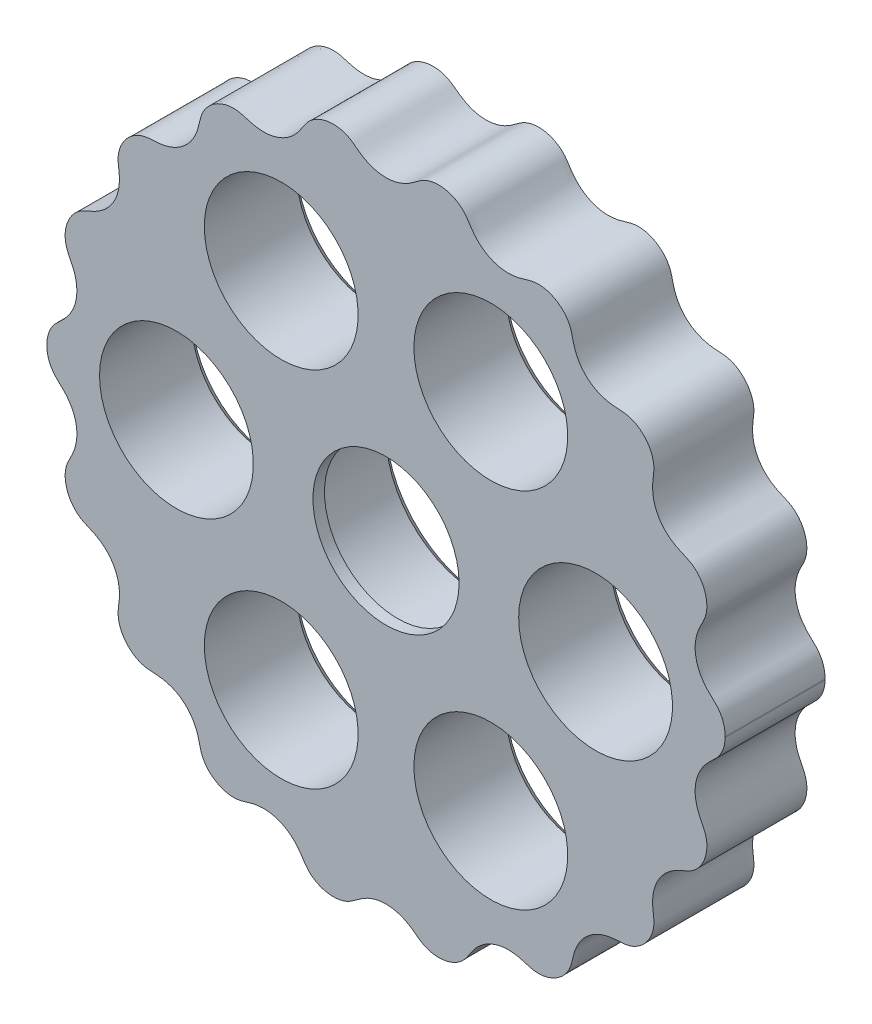
SolidWorks part; units mm, degrees
ref_plane "Front Plane" through (0, 0, 0) normal (0, 0, 1) x (1, 0, 0)
ref_plane "Top Plane" through (0, 0, 0) normal (0, 1, 0) x (1, 0, 0)
ref_plane "Right Plane" through (0, 0, 0) normal (1, 0, 0) x (0, 0, -1)
sketch "Sketch1" plane through (0, 0, 0) normal (0, 0, 1) x (1, 0, 0)
  arc A0 (44.0985, -0.1203) -> (44.1, 0) centre (39.3924, 0) ccw
  circle A1 centre (0, 0) radius 12
  circle A2 centre (27.25, 0) radius 10
  circle A3 centre (13.625, -23.5992) radius 10
  circle A4 centre (-13.625, -23.5992) radius 10
  circle A5 centre (-27.25, 0) radius 10
  circle A6 centre (-13.625, 23.5992) radius 10
  circle A7 centre (13.625, 23.5992) radius 10
  spline S0 degree 4 poles (36.6767, -18.9558) (36.8635, -18.7987) (37.1568, -18.579) (37.5707, -18.3184) (38.1155, -18.0434) (38.5626, -17.8474) (39.0142, -17.663) (39.4567, -17.456) (39.9012, -17.1807) (40.3307, -16.827) (40.8354, -16.2774) (41.3043, -15.523) (41.6465, -14.5868) (41.7649, -13.5582) (41.6813, -12.7422) (41.4951, -12.1162) (41.2986, -11.6694) (41.1215, -11.3218) (40.8977, -10.8888) (40.649, -10.3583) (40.4142, -9.7146) (40.1974, -8.7592) (40.1486, -7.6129) (40.3906, -6.3196) (40.9635, -5.1322) (41.587, -4.3265) (42.1201, -3.7892) (42.487, -3.4498) (42.7801, -3.1781) (43.1277, -2.8182) (43.4078, -2.4428) (43.6222, -2.0645) (43.7821, -1.6974) (43.8734, -1.446) (43.9495, -1.19) (44.0102, -0.9293) (44.0501, -0.6984) (44.0747, -0.5033) (44.0889, -0.3315) (44.0965, -0.1882) (44.1004, -0.0512) (44.1003, 0.0575) (44.0961, 0.2002) (44.0877, 0.3516) (44.0718, 0.5312) (44.0443, 0.7371) (44.0062, 0.9465) (43.9574, 1.1527) (43.9002, 1.3564) (43.8124, 1.6248) (43.6759, 1.9561) (43.4704, 2.3388) (43.1973, 2.7268) (42.9028, 3.0591) (42.5811, 3.3642) (42.2543, 3.6633) (41.857, 4.0496) (41.4472, 4.5088) (41.0516, 5.0585) (40.6188, 5.8583) (40.2694, 6.862) (40.1379, 7.9369) (40.2404, 9.0241) (40.4824, 9.9238) (40.7241, 10.5303) (40.9711, 11.0329) (41.23, 11.5305) (41.4742, 12.0369) (41.6912, 12.7506) (41.7643, 13.6759) (41.6231, 14.6695) (41.2345, 15.6741) (40.6786, 16.4957) (40.0904, 17.0544) (39.5529, 17.4028) (39.1287, 17.6105) (38.7812, 17.7582) (38.3459, 17.9401) (37.6896, 18.2421) (36.8537, 18.748) (35.9651, 19.5642) (35.2253, 20.6754) (34.8042, 21.8218) (34.6582, 22.7995) (34.6551, 23.5837) (34.7014, 24.1649) (34.7588, 24.6276) (34.819, 25.0899) (34.8465, 25.5562) (34.8182, 26.0519) (34.7221, 26.5691) (34.5055, 27.2363) (34.094, 28.0103) (33.4389, 28.7967) (32.6453, 29.3765) (31.9237, 29.701) (31.3397, 29.8541) (30.9247, 29.9174) (30.5063, 29.9454) (30.0877, 29.9633) (29.5648, 29.9977) (28.7961, 30.0962) (27.8011, 30.3642) (26.6402, 30.9641) (25.5501, 31.9548) (24.8466, 33.0536) (24.4844, 34.0219) (24.3027, 34.7493) (24.1799, 35.3002) (24.0444, 35.8492) (23.7558, 36.5419) (23.2182, 37.3055) (22.4721, 37.981) (21.5304, 38.5043) (20.5803, 38.7796) (19.7758, 38.834) (19.1432, 38.7607) (18.6866, 38.6509) (18.3273, 38.5424) (17.8796, 38.4022) (17.1879, 38.2098) (16.2295, 38.0541) (15.1511, 38.0927) (14.1001, 38.3568) (13.249, 38.7395) (12.5843, 39.159) (11.9777, 39.6706) (11.5076, 40.1878) (11.1477, 40.6723) (10.8676, 41.0971) (10.6491, 41.4405) (10.4195, 41.7769) (10.1616, 42.0928) (9.8452, 42.4081) (9.4641, 42.7096) (8.8955, 43.0565) (8.1021, 43.3731) (7.1136, 43.5515) (6.147, 43.4906) (5.3888, 43.281) (4.8443, 43.0283) (4.4861, 42.8141) (4.1483, 42.5698) (3.8181, 42.3158) (3.399, 42.0065) (2.753, 41.5865) (1.827, 41.1474) (0.5868, 40.8561) (-0.8258, 40.8878) (-2.0369, 41.2268) (-2.9229, 41.6848) (-3.5391, 42.1066) (-3.9385, 42.4083) (-4.2568, 42.6512) (-4.5868, 42.8786) (-4.9366, 43.0749) (-5.4733, 43.3086) (-6.2224, 43.5002) (-7.1565, 43.5453) (-8.2308, 43.3442) (-9.1419, 42.9461) (-9.7919, 42.4774) (-10.2304, 42.0207) (-10.5107, 41.6472) (-10.716, 41.3356) (-10.9671, 40.9426) (-11.3683, 40.3523) (-11.9933, 39.6173) (-12.9784, 38.8345) (-14.3072, 38.2427) (-15.622, 38.0386) (-16.7078, 38.119) (-17.5001, 38.2943) (-18.0183, 38.4446) (-18.4296, 38.575) (-18.8445, 38.6948) (-19.2689, 38.7773) (-19.7296, 38.8158) (-20.2217, 38.799) (-20.8742, 38.6969) (-21.6651, 38.435) (-22.5148, 37.9532) (-23.2004, 37.3139) (-23.6407, 36.7001) (-23.8979, 36.1889) (-24.0388, 35.8228) (-24.1457, 35.4456) (-24.2324, 35.0637) (-24.341, 34.5862) (-24.5432, 33.8399) (-24.9478, 32.8575) (-25.7396, 31.7268) (-26.8198, 30.8543) (-27.9055, 30.3412) (-28.8681, 30.0882) (-29.542, 29.9965) (-30.1085, 29.9625) (-30.655, 29.9382) (-31.2013, 29.8918) (-31.908, 29.7209) (-32.7236, 29.3297) (-33.437, 28.7738) (-34.0217, 28.0893) (-34.4319, 27.3875) (-34.6947, 26.7092) (-34.8184, 26.0998) (-34.8448, 25.586) (-34.8229, 25.1791) (-34.7914, 24.879) (-34.753, 24.5799) (-34.7164, 24.2805) (-34.6791, 23.9054) (-34.6547, 23.4533) (-34.6644, 22.9248) (-34.752, 22.1746) (-34.9928, 21.2469) (-35.4949, 20.1956) (-36.285, 19.2336) (-37.1129, 18.5857) (-37.8164, 18.1869) (-38.3337, 17.9455) (-38.7546, 17.7691) (-39.1754, 17.5922) (-39.5824, 17.3838) (-39.9866, 17.1147) (-40.376, 16.7794) (-40.8341, 16.2703) (-41.287, 15.5514) (-41.6373, 14.6281) (-41.7684, 13.5957) (-41.6841, 12.7484) (-41.4922, 12.1084) (-41.2953, 11.6627) (-41.1183, 11.3156) (-40.8949, 10.8831) (-40.6493, 10.3583) (-40.4186, 9.7263) (-40.2044, 8.7952) (-40.1455, 7.6523) (-40.3811, 6.3316) (-40.9655, 5.1189) (-41.6171, 4.2907) (-42.1615, 3.7501) (-42.5188, 3.4208) (-42.8029, 3.1556) (-43.1388, 2.8039) (-43.5356, 2.2681) (-43.902, 1.5016) (-44.1301, 0.4873) (-44.1153, -0.4997) (-43.9342, -1.3305) (-43.676, -1.9663) (-43.4233, -2.4149) (-43.1338, -2.8061) (-42.8211, -3.1409) (-42.4852, -3.4513) (-42.1496, -3.7619) (-41.7459, -4.1672) (-41.2216, -4.785) (-40.6667, -5.6805) (-40.2571, -6.8575) (-40.1492, -8.0179) (-40.2435, -8.9709) (-40.4198, -9.7036) (-40.5923, -10.2019) (-40.7703, -10.617) (-40.9338, -10.9558) (-41.0705, -11.2238) (-41.2084, -11.4912) (-41.3399, -11.762) (-41.4983, -12.1364) (-41.6474, -12.6276) (-41.7379, -13.2414) (-41.7216, -13.967) (-41.5738, -14.7731) (-41.2501, -15.6297) (-40.7493, -16.4152) (-40.1472, -17.0103) (-39.5948, -17.3794) (-39.1613, -17.5962) (-38.805, -17.7483) (-38.3581, -17.9346) (-37.6632, -18.2533) (-36.7684, -18.8026) (-35.9394, -19.6017) (-35.3162, -20.559) (-34.9501, -21.4361) (-34.754, -22.1735) (-34.6561, -22.9355) (-34.6539, -23.6107) (-34.7037, -24.19) (-34.7654, -24.6746) (-34.814, -25.0624) (-34.8415, -25.4527) (-34.8332, -25.844) (-34.765, -26.411) (-34.56, -27.1363) (-34.1301, -27.9767) (-33.4866, -28.7263) (-32.8171, -29.248) (-32.2156, -29.5706) (-31.7373, -29.7537) (-31.2675, -29.87) (-30.8155, -29.9284) (-30.361, -29.9515) (-29.9067, -29.9728) (-29.3398, -30.0211) (-28.5445, -30.1517) (-27.5467, -30.4714) (-26.4782, -31.095) (-25.6473, -31.8986) (-25.1024, -32.6745) (-24.7614, -33.3361) (-24.5688, -33.82) (-24.4344, -34.2453) (-24.3393, -34.6045) (-24.2708, -34.8937) (-24.2056, -35.1836) (-24.1369, -35.4728) (-24.0508, -35.7776) (-23.9368, -36.0939) (-23.7481, -36.5019) (-23.4494, -36.98) (-23.0222, -37.4813) (-22.3719, -38.029) (-21.544, -38.4954) (-20.7168, -38.7507) (-19.9455, -38.8252) (-19.36, -38.7875) (-18.9635, -38.7214) (-18.575, -38.6194) (-18.1922, -38.4994) (-17.7124, -38.3527) (-16.9871, -38.1681) (-15.9954, -38.0433) (-14.7404, -38.1435) (-13.4038, -38.602) (-12.3415, -39.3031) (-11.6253, -40.033) (-11.1642, -40.6483) (-10.8775, -41.0818) (-10.6541, -41.4324) (-10.3623, -41.8626) (-9.899, -42.3938) (-9.1869, -42.9321) (-8.2037, -43.3602) (-7.0734, -43.5529) (-6.1148, -43.4841) (-5.3713, -43.274) (-4.8379, -43.0245) (-4.4874, -42.8146) (-4.1564, -42.5758) (-3.8331, -42.3273) (-3.4233, -42.0238) (-2.7537, -41.584) (-1.7612, -41.114) (-0.4425, -40.8308) (1.0403, -40.9203) (2.2524, -41.3176) (3.0965, -41.7927) (3.6787, -42.2102) (4.0505, -42.4945) (4.3506, -42.7186) (4.7419, -42.9762) (5.3109, -43.2592) (6.0842, -43.4809) (7.0779, -43.5461) (8.1565, -43.3701) (9.0185, -43.0112) (9.656, -42.5787) (10.0808, -42.1789) (10.3429, -41.8772) (10.5757, -41.5527) (10.7913, -41.217) (11.062, -40.7981) (11.4933, -40.1917) (12.1633, -39.458) (13.1794, -38.7205) (14.4926, -38.1994) (15.7586, -38.0413) (16.7829, -38.1326) (17.5369, -38.3043) (18.0387, -38.4511) (18.4373, -38.5773) (18.8393, -38.693) (19.2503, -38.7741) (19.7068, -38.8152) (20.2045, -38.8013) (20.8784, -38.6982) (21.7056, -38.4205) (22.4637, -37.9777) (23.1147, -37.3897) (23.5463, -36.8348) (23.8129, -36.3801) (24.0082, -35.9224) (24.1409, -35.4736) (24.2423, -35.0176) (24.3472, -34.5622) (24.5038, -33.9993) (24.7774, -33.2626) (25.2526, -32.3934) (26.0445, -31.4622) (27.1225, -30.6755) (28.2369, -30.2168) (29.1936, -30.0303) (29.912, -29.9724) (30.3823, -29.9506) (30.7585, -29.9304) (31.2269, -29.8792) (31.8494, -29.734) (32.5908, -29.4093) (33.3924, -28.8267) (34.1, -28.0146) (34.5716, -27.1275) (34.818, -26.2303) (34.8559, -25.4836) (34.798, -24.9232) (34.725, -24.3656) (34.6454, -23.6229) (34.6499, -22.5928) (34.9244, -21.3341) (35.5841, -20.0498) (36.4432, -19.0874) (37.2687, -18.4847) (37.9615, -18.1146) (38.4661, -17.8887) (38.8747, -17.7199) (39.2802, -17.5429) (39.6692, -17.3307) (40.0569, -17.059) (40.4321, -16.7224) (40.8754, -16.2125) (41.3225, -15.4793) (41.6159, -14.6641) (41.7389, -13.805) (41.7166, -13.1062) (41.6324, -12.5888) (41.4921, -12.1142) (41.3092, -11.6862) (41.0959, -11.2734) (40.8838, -10.86) (40.6409, -10.3322) (40.3736, -9.5978) (40.1722, -8.6335) (40.1685, -7.4139) (40.4758, -6.1143) (41.0266, -5.0381) (41.638, -4.2711) (42.152, -3.7595) (42.4998, -3.4381) (42.7773, -3.1801) (43.1073, -2.8399) (43.4176, -2.4332) (43.6529, -2.012) (43.8242, -1.5939) (43.9238, -1.2824) (43.9889, -1.0282) (44.033, -0.8034) (44.0616, -0.6126) (44.0796, -0.4441) (44.0904, -0.304) (44.0975, -0.1709) (44.1002, -0.0646) (44.0998, 0.0735) (44.0955, 0.2206) (44.0851, 0.3964) (44.0643, 0.597) (44.0285, 0.8351) (43.9716, 1.1035) (43.8986, 1.3677) (43.8096, 1.6271) (43.6583, 1.9911) (43.4135, 2.4438) (43.0871, 2.8775) (42.6816, 3.2715) (42.2656, 3.653) (41.7268, 4.1708) (41.0686, 4.9615) (40.4759, 6.0882) (40.1559, 7.4652) (40.1801, 8.7282) (40.4033, 9.7014) (40.6813, 10.4269) (40.92, 10.9322) (41.1253, 11.3291) (41.3284, 11.7273) (41.5005, 12.1406) (41.6361, 12.607) (41.7187, 13.1243) (41.7383, 13.8359) (41.6034, 14.7228) (41.2341, 15.7008) (40.6514, 16.5314) (40.0399, 17.0906) (39.4907, 17.4365) (39.0646, 17.6413) (38.6279, 17.8207) (38.1942, 18.0075) (37.6639, 18.2672) (37.259, 18.512) (36.9707, 18.7184) (36.7863, 18.8659) knots 0 0 0 0 0 0.002836 0.004253 0.005671 0.007089 0.008507 0.009925 0.011343 0.013148 0.014954 0.018566 0.021594 0.024621 0.026888 0.028021 0.029155 0.030288 0.031421 0.033688 0.03596 0.038232 0.042776 0.046922 0.051068 0.053391 0.054552 0.055714 0.056876 0.058037 0.060361 0.061137 0.061913 0.062689 0.063466 0.064242 0.065018 0.065406 0.065795 0.066183 0.066571 0.066981 0.067391 0.067801 0.068211 0.069031 0.069851 0.070261 0.070671 0.071491 0.073132 0.074419 0.075707 0.076995 0.078282 0.07957 0.080858 0.083433 0.085425 0.087418 0.091402 0.095715 0.097871 0.100027 0.102202 0.103289 0.104376 0.106551 0.108726 0.111902 0.115078 0.118109 0.12114 0.123333 0.12443 0.125527 0.126624 0.127721 0.129914 0.133921 0.137927 0.141605 0.145284 0.147993 0.149348 0.150703 0.152057 0.153412 0.154767 0.156121 0.157815 0.159508 0.162895 0.166245 0.169595 0.170813 0.17203 0.173248 0.174466 0.175684 0.176902 0.179337 0.183463 0.187589 0.191926 0.196263 0.19845 0.199544 0.200638 0.202826 0.205013 0.208208 0.211403 0.214416 0.217428 0.219609 0.2207 0.22179 0.222881 0.223971 0.226152 0.230133 0.234114 0.236391 0.238667 0.240943 0.24322 0.245585 0.246768 0.247951 0.249134 0.250316 0.251499 0.252682 0.254316 0.255951 0.25922 0.262551 0.265882 0.267093 0.268303 0.269514 0.270725 0.271935 0.273146 0.275567 0.279672 0.283776 0.287796 0.291816 0.294143 0.295306 0.29647 0.297633 0.298797 0.29996 0.301124 0.304426 0.307727 0.310722 0.313717 0.315886 0.31697 0.318054 0.319138 0.320223 0.322391 0.326347 0.330303 0.334707 0.33911 0.341618 0.342872 0.344126 0.34538 0.346634 0.347888 0.349142 0.350743 0.352343 0.355544 0.35877 0.361996 0.363134 0.364272 0.36541 0.366548 0.367686 0.368824 0.3711 0.375531 0.379962 0.384669 0.387023 0.389377 0.391497 0.392557 0.393618 0.395738 0.397859 0.400955 0.404052 0.406156 0.40826 0.410365 0.412469 0.413345 0.414222 0.415098 0.415975 0.416851 0.417727 0.41948 0.421233 0.422985 0.426491 0.43057 0.434649 0.437302 0.438628 0.439954 0.44128 0.442607 0.443933 0.445259 0.446911 0.448564 0.451868 0.455076 0.458283 0.460547 0.461678 0.46281 0.463942 0.465074 0.467337 0.46954 0.471743 0.476148 0.480544 0.48494 0.487199 0.488328 0.489458 0.490587 0.491717 0.493975 0.497176 0.500376 0.503687 0.505343 0.506999 0.508328 0.509657 0.510985 0.512314 0.513643 0.514972 0.51763 0.521717 0.525805 0.529302 0.531051 0.5328 0.534548 0.535423 0.536297 0.537171 0.538046 0.53892 0.539794 0.541894 0.543993 0.546093 0.548193 0.551381 0.55457 0.556821 0.557947 0.559072 0.560198 0.561324 0.563575 0.567955 0.572335 0.574545 0.576756 0.578967 0.581177 0.583449 0.584584 0.58572 0.586856 0.587991 0.589127 0.590263 0.593481 0.5967 0.599994 0.601641 0.603287 0.604609 0.605931 0.607253 0.608575 0.609897 0.611219 0.613863 0.617928 0.621994 0.625448 0.627175 0.628902 0.630629 0.631492 0.632356 0.63322 0.634083 0.634947 0.63581 0.636899 0.637987 0.640164 0.64234 0.644517 0.647826 0.651135 0.652301 0.653467 0.654633 0.655799 0.656965 0.658131 0.660463 0.664492 0.668521 0.672617 0.676713 0.679129 0.680337 0.681545 0.682753 0.683961 0.686377 0.689701 0.693025 0.6963 0.699576 0.700761 0.701947 0.703132 0.704317 0.705502 0.706687 0.709058 0.71362 0.718182 0.722153 0.726125 0.728301 0.729389 0.730477 0.731565 0.732653 0.73483 0.737836 0.740842 0.744132 0.747422 0.748581 0.74974 0.7509 0.752059 0.753218 0.754378 0.756697 0.760702 0.764708 0.768825 0.772943 0.775373 0.776588 0.777804 0.779019 0.780234 0.781449 0.782664 0.784335 0.786007 0.789349 0.792743 0.79444 0.796137 0.797495 0.798852 0.80021 0.801567 0.802925 0.804282 0.806998 0.810684 0.81437 0.818367 0.822363 0.824552 0.825646 0.826741 0.827835 0.82893 0.831119 0.834143 0.837166 0.84035 0.843533 0.845713 0.847892 0.848982 0.850072 0.852251 0.856573 0.860895 0.864871 0.868848 0.871417 0.872702 0.873987 0.875272 0.876557 0.877842 0.879127 0.880763 0.8824 0.885674 0.889049 0.890737 0.892425 0.893775 0.895125 0.896475 0.897825 0.899175 0.900525 0.903225 0.906891 0.910557 0.914579 0.9186 0.920802 0.921903 0.923004 0.924105 0.925206 0.927407 0.928928 0.929689 0.930449 0.93121 0.93197 0.93235 0.93273 0.933111 0.933491 0.933889 0.934287 0.934686 0.935084 0.93588 0.936677 0.937473 0.938269 0.939066 0.939862 0.94205 0.944237 0.945331 0.946425 0.948612 0.952921 0.957229 0.96105 0.964871 0.967468 0.968766 0.970065 0.971364 0.972662 0.973961 0.97526 0.976997 0.978734 0.982209 0.985617 0.989025 0.990397 0.991769 0.99314 0.994512 0.995884 0.997256 1 1 1 1 1 construction
  spline S1 degree 4 poles (44.1, 0) (44.1, 0.0306) (44.0993, 0.0917) (44.0961, 0.2002) (44.0877, 0.3516) (44.0718, 0.5312) (44.0443, 0.7371) (44.0062, 0.9465) (43.9574, 1.1527) (43.9002, 1.3564) (43.8124, 1.6248) (43.6759, 1.9561) (43.4704, 2.3388) (43.1973, 2.7268) (42.9028, 3.0591) (42.5811, 3.3642) (42.2543, 3.6633) (41.857, 4.0496) (41.4472, 4.5088) (41.0516, 5.0585) (40.6188, 5.8583) (40.2694, 6.862) (40.1379, 7.9369) (40.2404, 9.0241) (40.4824, 9.9238) (40.7241, 10.5303) (40.9711, 11.0329) (41.23, 11.5305) (41.4742, 12.0369) (41.6912, 12.7506) (41.7643, 13.6759) (41.6231, 14.6695) (41.2345, 15.6741) (40.6786, 16.4957) (40.0904, 17.0544) (39.5529, 17.4028) (39.1287, 17.6105) (38.7812, 17.7582) (38.3459, 17.9401) (37.6896, 18.2421) (36.8537, 18.748) (35.9651, 19.5642) (35.2253, 20.6754) (34.8042, 21.8218) (34.6582, 22.7995) (34.6551, 23.5837) (34.7014, 24.1649) (34.7588, 24.6276) (34.819, 25.0899) (34.8465, 25.5562) (34.8182, 26.0519) (34.7221, 26.5691) (34.5055, 27.2363) (34.094, 28.0103) (33.4389, 28.7967) (32.6453, 29.3765) (31.9237, 29.701) (31.3397, 29.8541) (30.9247, 29.9174) (30.5063, 29.9454) (30.0877, 29.9633) (29.5648, 29.9977) (28.7961, 30.0962) (27.8011, 30.3642) (26.6402, 30.9641) (25.5501, 31.9548) (24.8466, 33.0536) (24.4844, 34.0219) (24.3027, 34.7493) (24.1799, 35.3002) (24.0444, 35.8492) (23.7558, 36.5419) (23.2182, 37.3055) (22.4721, 37.981) (21.5304, 38.5043) (20.5803, 38.7796) (19.7758, 38.834) (19.1432, 38.7607) (18.6866, 38.6509) (18.3273, 38.5424) (17.8796, 38.4022) (17.1879, 38.2098) (16.2295, 38.0541) (15.1511, 38.0927) (14.1001, 38.3568) (13.249, 38.7395) (12.5843, 39.159) (11.9777, 39.6706) (11.5076, 40.1878) (11.1477, 40.6723) (10.8676, 41.0971) (10.6491, 41.4405) (10.4195, 41.7769) (10.1616, 42.0928) (9.8452, 42.4081) (9.4641, 42.7096) (8.8955, 43.0565) (8.1021, 43.3731) (7.1136, 43.5515) (6.147, 43.4906) (5.3888, 43.281) (4.8443, 43.0283) (4.4861, 42.8141) (4.1483, 42.5698) (3.8181, 42.3158) (3.399, 42.0065) (2.753, 41.5865) (1.827, 41.1474) (0.5868, 40.8561) (-0.8258, 40.8878) (-2.0369, 41.2268) (-2.9229, 41.6848) (-3.5391, 42.1066) (-3.9385, 42.4083) (-4.2568, 42.6512) (-4.5868, 42.8786) (-4.9366, 43.0749) (-5.4733, 43.3086) (-6.2224, 43.5002) (-7.1565, 43.5453) (-8.2308, 43.3442) (-9.1419, 42.9461) (-9.7919, 42.4774) (-10.2304, 42.0207) (-10.5107, 41.6472) (-10.716, 41.3356) (-10.9671, 40.9426) (-11.3683, 40.3523) (-11.9933, 39.6173) (-12.9784, 38.8345) (-14.3072, 38.2427) (-15.622, 38.0386) (-16.7078, 38.119) (-17.5001, 38.2943) (-18.0183, 38.4446) (-18.4296, 38.575) (-18.8445, 38.6948) (-19.2689, 38.7773) (-19.7296, 38.8158) (-20.2217, 38.799) (-20.8742, 38.6969) (-21.6651, 38.435) (-22.5148, 37.9532) (-23.2004, 37.3139) (-23.6407, 36.7001) (-23.8979, 36.1889) (-24.0388, 35.8228) (-24.1457, 35.4456) (-24.2324, 35.0637) (-24.341, 34.5862) (-24.5432, 33.8399) (-24.9478, 32.8575) (-25.7396, 31.7268) (-26.8198, 30.8543) (-27.9055, 30.3412) (-28.8681, 30.0882) (-29.542, 29.9965) (-30.1085, 29.9625) (-30.655, 29.9382) (-31.2013, 29.8918) (-31.908, 29.7209) (-32.7236, 29.3297) (-33.437, 28.7738) (-34.0217, 28.0893) (-34.4319, 27.3875) (-34.6947, 26.7092) (-34.8184, 26.0998) (-34.8448, 25.586) (-34.8229, 25.1791) (-34.7914, 24.879) (-34.753, 24.5799) (-34.7164, 24.2805) (-34.6791, 23.9054) (-34.6547, 23.4533) (-34.6644, 22.9248) (-34.752, 22.1746) (-34.9928, 21.2469) (-35.4949, 20.1956) (-36.285, 19.2336) (-37.1129, 18.5857) (-37.8164, 18.1869) (-38.3337, 17.9455) (-38.7546, 17.7691) (-39.1754, 17.5922) (-39.5824, 17.3838) (-39.9866, 17.1147) (-40.376, 16.7794) (-40.8341, 16.2703) (-41.287, 15.5514) (-41.6373, 14.6281) (-41.7684, 13.5957) (-41.6841, 12.7484) (-41.4922, 12.1084) (-41.2953, 11.6627) (-41.1183, 11.3156) (-40.8949, 10.8831) (-40.6493, 10.3583) (-40.4186, 9.7263) (-40.2044, 8.7952) (-40.1455, 7.6523) (-40.3811, 6.3316) (-40.9655, 5.1189) (-41.6171, 4.2907) (-42.1615, 3.7501) (-42.5188, 3.4208) (-42.8029, 3.1556) (-43.1388, 2.8039) (-43.5356, 2.2681) (-43.902, 1.5016) (-44.1301, 0.4873) (-44.1153, -0.4997) (-43.9342, -1.3305) (-43.676, -1.9663) (-43.4233, -2.4149) (-43.1338, -2.8061) (-42.8211, -3.1409) (-42.4852, -3.4513) (-42.1496, -3.7619) (-41.7459, -4.1672) (-41.2216, -4.785) (-40.6667, -5.6805) (-40.2571, -6.8575) (-40.1492, -8.0179) (-40.2435, -8.9709) (-40.4198, -9.7036) (-40.5923, -10.2019) (-40.7703, -10.617) (-40.9338, -10.9558) (-41.0705, -11.2238) (-41.2084, -11.4912) (-41.3399, -11.762) (-41.4983, -12.1364) (-41.6474, -12.6276) (-41.7379, -13.2414) (-41.7216, -13.967) (-41.5738, -14.7731) (-41.2501, -15.6297) (-40.7493, -16.4152) (-40.1472, -17.0103) (-39.5948, -17.3794) (-39.1613, -17.5962) (-38.805, -17.7483) (-38.3581, -17.9346) (-37.6632, -18.2533) (-36.7684, -18.8026) (-35.9394, -19.6017) (-35.3162, -20.559) (-34.9501, -21.4361) (-34.754, -22.1735) (-34.6561, -22.9355) (-34.6539, -23.6107) (-34.7037, -24.19) (-34.7654, -24.6746) (-34.814, -25.0624) (-34.8415, -25.4527) (-34.8332, -25.844) (-34.765, -26.411) (-34.56, -27.1363) (-34.1301, -27.9767) (-33.4866, -28.7263) (-32.8171, -29.248) (-32.2156, -29.5706) (-31.7373, -29.7537) (-31.2675, -29.87) (-30.8155, -29.9284) (-30.361, -29.9515) (-29.9067, -29.9728) (-29.3398, -30.0211) (-28.5445, -30.1517) (-27.5467, -30.4714) (-26.4782, -31.095) (-25.6473, -31.8986) (-25.1024, -32.6745) (-24.7614, -33.3361) (-24.5688, -33.82) (-24.4344, -34.2453) (-24.3393, -34.6045) (-24.2708, -34.8937) (-24.2056, -35.1836) (-24.1369, -35.4728) (-24.0508, -35.7776) (-23.9368, -36.0939) (-23.7481, -36.5019) (-23.4494, -36.98) (-23.0222, -37.4813) (-22.3719, -38.029) (-21.544, -38.4954) (-20.7168, -38.7507) (-19.9455, -38.8252) (-19.36, -38.7875) (-18.9635, -38.7214) (-18.575, -38.6194) (-18.1922, -38.4994) (-17.7124, -38.3527) (-16.9871, -38.1681) (-15.9954, -38.0433) (-14.7404, -38.1435) (-13.4038, -38.602) (-12.3415, -39.3031) (-11.6253, -40.033) (-11.1642, -40.6483) (-10.8775, -41.0818) (-10.6541, -41.4324) (-10.3623, -41.8626) (-9.899, -42.3938) (-9.1869, -42.9321) (-8.2037, -43.3602) (-7.0734, -43.5529) (-6.1148, -43.4841) (-5.3713, -43.274) (-4.8379, -43.0245) (-4.4874, -42.8146) (-4.1564, -42.5758) (-3.8331, -42.3273) (-3.4233, -42.0238) (-2.7537, -41.584) (-1.7612, -41.114) (-0.4425, -40.8308) (1.0403, -40.9203) (2.2524, -41.3176) (3.0965, -41.7927) (3.6787, -42.2102) (4.0505, -42.4945) (4.3506, -42.7186) (4.7419, -42.9762) (5.3109, -43.2592) (6.0842, -43.4809) (7.0779, -43.5461) (8.1565, -43.3701) (9.0185, -43.0112) (9.656, -42.5787) (10.0808, -42.1789) (10.3429, -41.8772) (10.5757, -41.5527) (10.7913, -41.217) (11.062, -40.7981) (11.4933, -40.1917) (12.1633, -39.458) (13.1794, -38.7205) (14.4926, -38.1994) (15.7586, -38.0413) (16.7829, -38.1326) (17.5369, -38.3043) (18.0387, -38.4511) (18.4373, -38.5773) (18.8393, -38.693) (19.2503, -38.7741) (19.7068, -38.8152) (20.2045, -38.8013) (20.8784, -38.6982) (21.7056, -38.4205) (22.4637, -37.9777) (23.1147, -37.3897) (23.5463, -36.8348) (23.8129, -36.3801) (24.0082, -35.9224) (24.1409, -35.4736) (24.2423, -35.0176) (24.3472, -34.5622) (24.5038, -33.9993) (24.7774, -33.2626) (25.2526, -32.3934) (26.0445, -31.4622) (27.1225, -30.6755) (28.2369, -30.2168) (29.1936, -30.0303) (29.912, -29.9724) (30.3823, -29.9506) (30.7585, -29.9304) (31.2269, -29.8792) (31.8494, -29.734) (32.5908, -29.4093) (33.3924, -28.8267) (34.1, -28.0146) (34.5716, -27.1275) (34.818, -26.2303) (34.8559, -25.4836) (34.798, -24.9232) (34.725, -24.3656) (34.6454, -23.6229) (34.6499, -22.5928) (34.9244, -21.3341) (35.5841, -20.0498) (36.4432, -19.0874) (37.2687, -18.4847) (37.9615, -18.1146) (38.4661, -17.8887) (38.8747, -17.7199) (39.2802, -17.5429) (39.6692, -17.3307) (40.0569, -17.059) (40.4321, -16.7224) (40.8754, -16.2125) (41.3225, -15.4793) (41.6159, -14.6641) (41.7389, -13.805) (41.7166, -13.1062) (41.6324, -12.5888) (41.4921, -12.1142) (41.3092, -11.6862) (41.0959, -11.2734) (40.8838, -10.86) (40.6409, -10.3322) (40.3736, -9.5978) (40.1722, -8.6335) (40.1685, -7.4139) (40.4758, -6.1143) (41.0266, -5.0381) (41.638, -4.2711) (42.152, -3.7595) (42.4998, -3.4381) (42.7773, -3.1801) (43.1073, -2.8399) (43.4176, -2.4332) (43.6529, -2.012) (43.8242, -1.5939) (43.9238, -1.2824) (43.9889, -1.0282) (44.033, -0.8034) (44.0616, -0.6126) (44.0796, -0.4441) (44.0904, -0.304) (44.0957, -0.2053) (44.0977, -0.1486) (44.0985, -0.1203) knots 0.066571 0.066571 0.066571 0.066571 0.066571 0.066981 0.067391 0.067801 0.068211 0.069031 0.069851 0.070261 0.070671 0.071491 0.073132 0.074419 0.075707 0.076995 0.078282 0.07957 0.080858 0.083433 0.085425 0.087418 0.091402 0.095715 0.097871 0.100027 0.102202 0.103289 0.104376 0.106551 0.108726 0.111902 0.115078 0.118109 0.12114 0.123333 0.12443 0.125527 0.126624 0.127721 0.129914 0.133921 0.137927 0.141605 0.145284 0.147993 0.149348 0.150703 0.152057 0.153412 0.154767 0.156121 0.157815 0.159508 0.162895 0.166245 0.169595 0.170813 0.17203 0.173248 0.174466 0.175684 0.176902 0.179337 0.183463 0.187589 0.191926 0.196263 0.19845 0.199544 0.200638 0.202826 0.205013 0.208208 0.211403 0.214416 0.217428 0.219609 0.2207 0.22179 0.222881 0.223971 0.226152 0.230133 0.234114 0.236391 0.238667 0.240943 0.24322 0.245585 0.246768 0.247951 0.249134 0.250316 0.251499 0.252682 0.254316 0.255951 0.25922 0.262551 0.265882 0.267093 0.268303 0.269514 0.270725 0.271935 0.273146 0.275567 0.279672 0.283776 0.287796 0.291816 0.294143 0.295306 0.29647 0.297633 0.298797 0.29996 0.301124 0.304426 0.307727 0.310722 0.313717 0.315886 0.31697 0.318054 0.319138 0.320223 0.322391 0.326347 0.330303 0.334707 0.33911 0.341618 0.342872 0.344126 0.34538 0.346634 0.347888 0.349142 0.350743 0.352343 0.355544 0.35877 0.361996 0.363134 0.364272 0.36541 0.366548 0.367686 0.368824 0.3711 0.375531 0.379962 0.384669 0.387023 0.389377 0.391497 0.392557 0.393618 0.395738 0.397859 0.400955 0.404052 0.406156 0.40826 0.410365 0.412469 0.413345 0.414222 0.415098 0.415975 0.416851 0.417727 0.41948 0.421233 0.422985 0.426491 0.43057 0.434649 0.437302 0.438628 0.439954 0.44128 0.442607 0.443933 0.445259 0.446911 0.448564 0.451868 0.455076 0.458283 0.460547 0.461678 0.46281 0.463942 0.465074 0.467337 0.46954 0.471743 0.476148 0.480544 0.48494 0.487199 0.488328 0.489458 0.490587 0.491717 0.493975 0.497176 0.500376 0.503687 0.505343 0.506999 0.508328 0.509657 0.510985 0.512314 0.513643 0.514972 0.51763 0.521717 0.525805 0.529302 0.531051 0.5328 0.534548 0.535423 0.536297 0.537171 0.538046 0.53892 0.539794 0.541894 0.543993 0.546093 0.548193 0.551381 0.55457 0.556821 0.557947 0.559072 0.560198 0.561324 0.563575 0.567955 0.572335 0.574545 0.576756 0.578967 0.581177 0.583449 0.584584 0.58572 0.586856 0.587991 0.589127 0.590263 0.593481 0.5967 0.599994 0.601641 0.603287 0.604609 0.605931 0.607253 0.608575 0.609897 0.611219 0.613863 0.617928 0.621994 0.625448 0.627175 0.628902 0.630629 0.631492 0.632356 0.63322 0.634083 0.634947 0.63581 0.636899 0.637987 0.640164 0.64234 0.644517 0.647826 0.651135 0.652301 0.653467 0.654633 0.655799 0.656965 0.658131 0.660463 0.664492 0.668521 0.672617 0.676713 0.679129 0.680337 0.681545 0.682753 0.683961 0.686377 0.689701 0.693025 0.6963 0.699576 0.700761 0.701947 0.703132 0.704317 0.705502 0.706687 0.709058 0.71362 0.718182 0.722153 0.726125 0.728301 0.729389 0.730477 0.731565 0.732653 0.73483 0.737836 0.740842 0.744132 0.747422 0.748581 0.74974 0.7509 0.752059 0.753218 0.754378 0.756697 0.760702 0.764708 0.768825 0.772943 0.775373 0.776588 0.777804 0.779019 0.780234 0.781449 0.782664 0.784335 0.786007 0.789349 0.792743 0.79444 0.796137 0.797495 0.798852 0.80021 0.801567 0.802925 0.804282 0.806998 0.810684 0.81437 0.818367 0.822363 0.824552 0.825646 0.826741 0.827835 0.82893 0.831119 0.834143 0.837166 0.84035 0.843533 0.845713 0.847892 0.848982 0.850072 0.852251 0.856573 0.860895 0.864871 0.868848 0.871417 0.872702 0.873987 0.875272 0.876557 0.877842 0.879127 0.880763 0.8824 0.885674 0.889049 0.890737 0.892425 0.893775 0.895125 0.896475 0.897825 0.899175 0.900525 0.903225 0.906891 0.910557 0.914579 0.9186 0.920802 0.921903 0.923004 0.924105 0.925206 0.927407 0.928928 0.929689 0.930449 0.93121 0.93197 0.93235 0.93273 0.933111 0.933491 0.933491 0.933491 0.933491 0.933491
  point P22 (0, 0)
  dimension "D1" = 24
  dimension "D2" = 20
  dimension "D3" = 27.25
  dimension "D4" = 6
extrude "Boss-Extrude1" add sketch "Sketch1" along normal mid plane 13
sketch "Sketch2" plane through (0, 0, 6.5) normal (0, 0, 1) x (1, 0, 0)
  circle A0 centre (0, 0) radius 12 construction
  circle A1 centre (0, 0) radius 12
  circle A2 centre (0, 0) radius 9.5
  dimension "D1" = 2.5
extrude "Boss-Extrude2" add sketch "Sketch2" against normal blind 1.5
chamfer "Chamfer1" distance 1 angle 45 7 edges at (-17.25, 0, -6.5) (-3.625, -23.5992, -6.5) (23.625, -23.5992, -6.5) (37.25, 0, -6.5) (12, 0, -6.5) (-3.625, 23.5992, -6.5) (23.625, 23.5992, -6.5)
